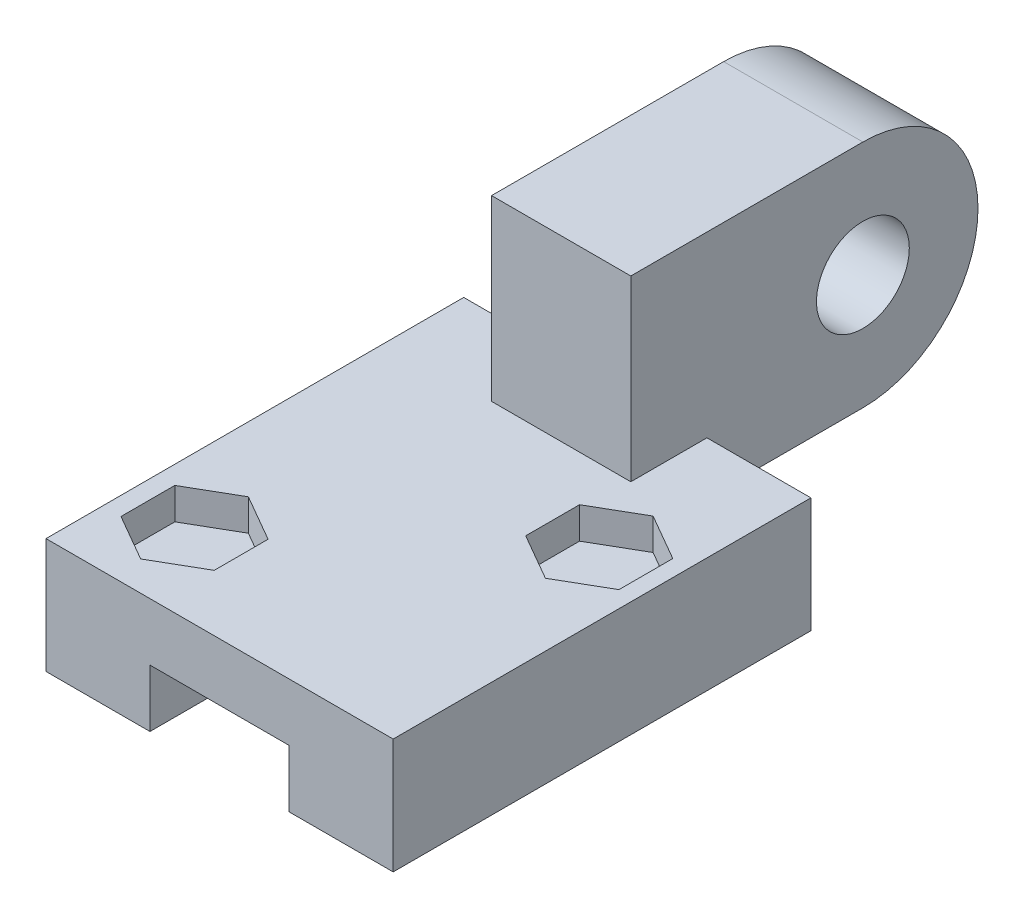
SolidWorks part; units mm, degrees
ref_plane "Alzado" through (0, 0, 0) normal (0, 0, 1) x (1, 0, 0)
ref_plane "Planta" through (0, 0, 0) normal (0, 1, 0) x (1, 0, 0)
ref_plane "Vista lateral" through (0, 0, 0) normal (1, 0, 0) x (0, 0, -1)
sketch "Croquis1" plane through (0, 0, 0) normal (0, 0, 1) x (1, 0, 0)
  line L0 (0.375, -0.31) -> (0.935, -0.31)
  line L1 (-0.935, 0.31) -> (0.935, 0.31)
  line L2 (-0.935, 0.31) -> (-0.935, -0.31)
  line L3 (-0.935, -0.31) -> (-0.375, -0.31)
  line L4 (0.935, 0.31) -> (0.935, -0.31)
  line L6 (-0.375, -0.31) -> (-0.375, 0)
  line L7 (-0.375, 0) -> (0.375, 0)
  line L8 (0.375, -0.31) -> (0.375, 0)
  point P8 (0, 0)
  dimension "D1" = 1.87
  dimension "D2" = 0.75
  dimension "D3" = 0.31
  dimension "D4" = 0.62
extrude "Saliente-Extruir2" add sketch "Croquis1" against normal blind 2.25
sketch "Croquis2" plane through (0, 0.31, 0) normal (0, 1, 0) x (1, 0, 0)
  line L7 (0.595, 1.16) -> (0.8461, 1.305)
  line L8 (0.8461, 1.305) -> (0.8461, 1.595)
  line L9 (0.8461, 1.595) -> (0.595, 1.74)
  line L10 (0.595, 1.74) -> (0.3439, 1.595)
  line L11 (0.3439, 1.595) -> (0.3439, 1.305)
  line L12 (0.3439, 1.305) -> (0.595, 1.16)
  line L18 (-0.935, 2.25) -> (-0.935, 0) construction
  line L19 (-0.585, 0.16) -> (-0.3339, 0.305)
  line L20 (-0.3339, 0.305) -> (-0.3339, 0.595)
  line L21 (-0.3339, 0.595) -> (-0.585, 0.74)
  line L22 (-0.585, 0.74) -> (-0.8361, 0.595)
  line L23 (-0.8361, 0.595) -> (-0.8361, 0.305)
  line L24 (-0.8361, 0.305) -> (-0.585, 0.16)
  line L25 (0.935, 0) -> (-0.935, 0) construction
  circle A0 centre (0.595, 1.45) radius 0.2511 construction
  circle A2 centre (-0.585, 0.45) radius 0.2511 construction
  point P1 (0, 0)
  point P13 (0, 0)
  point P14 (0, 0)
  point P16 (0, 0)
  point P24 (0, 0)
  point P25 (-0.3339, 0.595)
  point P26 (0, 0)
  point P27 (0.8461, 1.305)
  dimension "D1" = 0.29
  dimension "D2" = 0.29
  dimension "D3" = 1
  dimension "D4" = 0.35
  dimension "D5" = 0.45
  dimension "D6" = 1.18
extrude "Cortar-Extruir1" cut sketch "Croquis2" against normal blind 0.17
ref_plane "Plano1" through (0, 0, 0) normal (1, 0, 0) x (0, 0, -1)
sketch "Croquis3" plane through (0, 0, 0) normal (1, 0, 0) x (0, 0, -1)
  line L1 (1.84, 0.03) -> (3.09, 0.03)
  line L2 (1.84, 0.03) -> (1.84, 1.27)
  line L3 (1.84, 1.27) -> (3.09, 1.27)
  line L4 (2.25, -0.31) -> (2.25, 0.31) construction
  line L5 (2.25, 0.31) -> (0, 0.31) construction
  arc A0 (3.09, 1.27) -> (3.09, 0.03) centre (3.09, 0.65) cw
  circle A1 centre (3.09, 0.65) radius 0.25
  point P3 (0.9124, 0.31)
  point P9 (0, 0)
  point P12 (0, 0)
  dimension "D1" = 0.62
  dimension "D2" = 0.5
  dimension "D3" = 1.25
  dimension "D4" = 0.41
  dimension "D5" = 0.96
extrude "Saliente-Extruir4" add sketch "Croquis3" along normal mid plane 0.75
